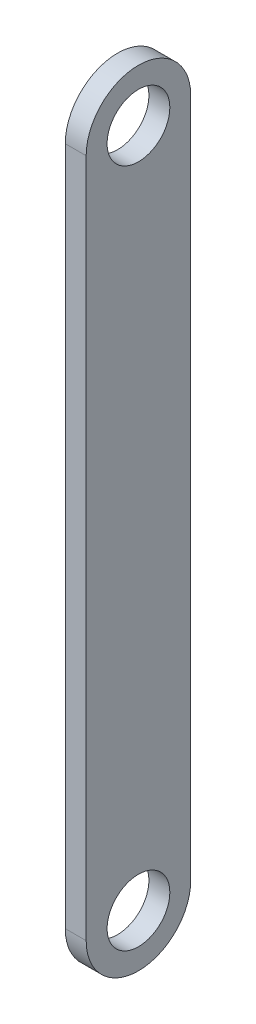
SolidWorks part; units mm, degrees
ref_plane "前视基准面" through (0, 0, 0) normal (0, 0, 1) x (1, 0, 0)
ref_plane "上视基准面" through (0, 0, 0) normal (0, 1, 0) x (1, 0, 0)
ref_plane "右视基准面" through (0, 0, 0) normal (1, 0, 0) x (0, 0, -1)
sketch "草图1" plane through (0, 0, 0) normal (1, 0, 0) x (0, 0, -1)
  line L0 (0, -32.5) -> (0, 32.5) construction
  line L1 (-5, -32.5) -> (-5, 32.5)
  line L2 (5, -32.5) -> (5, 32.5)
  arc A0 (-5, -32.5) -> (5, -32.5) centre (0, -32.5) ccw
  arc A1 (5, 32.5) -> (-5, 32.5) centre (0, 32.5) ccw
  circle A2 centre (0, 32.5) radius 3
  circle A3 centre (0, -32.5) radius 3
  point P2 (0, 0)
  dimension "D3" = 6
  dimension "D4" = 6
  dimension "D1" = 65
  dimension "D2" = 10
extrude "凸台-拉伸1" add sketch "草图1" along normal blind 2
